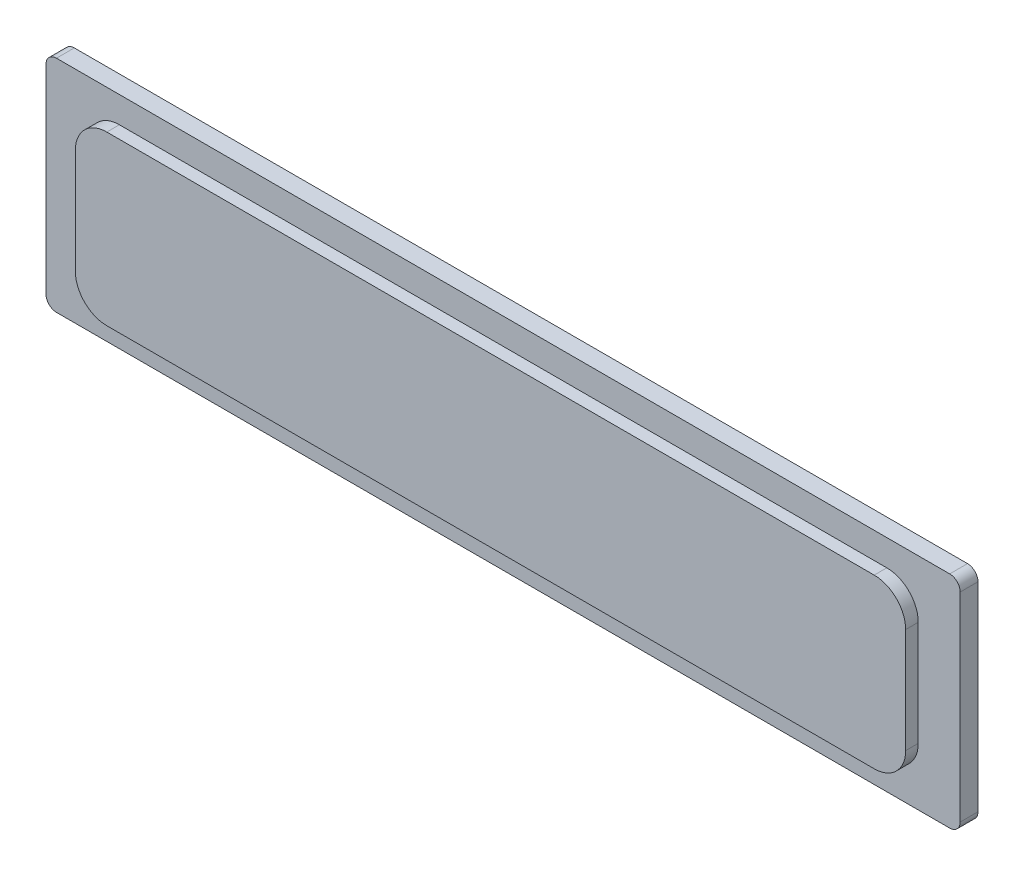
SolidWorks part; units mm, degrees
ref_plane "Спереди" through (0, 0, 0) normal (0, 0, 1) x (1, 0, 0)
ref_plane "Сверху" through (0, 0, 0) normal (0, 1, 0) x (1, 0, 0)
ref_plane "Справа" through (0, 0, 0) normal (1, 0, 0) x (0, 0, -1)
sketch "Эскиз1" plane through (0, 0, 0) normal (0, 0, 1) x (1, 0, 0)
  line L1 (-43.6, 10.5) -> (43.6, 10.5)
  line L2 (-43.6, 10.5) -> (-43.6, -10.5)
  line L3 (-43.6, -10.5) -> (43.6, -10.5)
  line L4 (43.6, 10.5) -> (43.6, -10.5)
  line L5 (-43.6, 10.5) -> (43.6, -10.5) construction
  line L6 (-43.6, -10.5) -> (43.6, 10.5) construction
  point P0 (0, 0)
  dimension "D1" = 21
  dimension "D2" = 87.2
extrude "Бобышка-Вытянуть1" add sketch "Эскиз1" along normal blind 1.7
sketch "Эскиз2" plane through (0, 0, 1.7) normal (0, 0, 1) x (1, 0, 0)
  line L0 (-43.6, -10.5) -> (43.6, -10.5) construction
  line L1 (-39.6, 8) -> (39.6, 8)
  line L2 (-39.6, 8) -> (-39.6, -8)
  line L3 (-39.6, -8) -> (39.6, -8)
  line L4 (39.6, 8) -> (39.6, -8)
  line L5 (-39.6, 8) -> (39.6, -8) construction
  line L6 (-39.6, -8) -> (39.6, 8) construction
  line L8 (43.6, -10.5) -> (43.6, 10.5) construction
  point P0 (0, 0)
  dimension "D1" = 2.5
  dimension "D2" = 4
extrude "Бобышка-Вытянуть2" add sketch "Эскиз2" along normal blind 1.2
fillet "Скругление1" radius 3 4 edges at (-39.6, -8, 2.3) (-39.6, 8, 2.3) (39.6, 8, 2.3) (39.6, -8, 2.3)
fillet "Скругление2" radius 1 4 edges at (43.6, -10.5, 0.85) (43.6, 10.5, 0.85) (-43.6, -10.5, 0.85) (-43.6, 10.5, 0.85)
